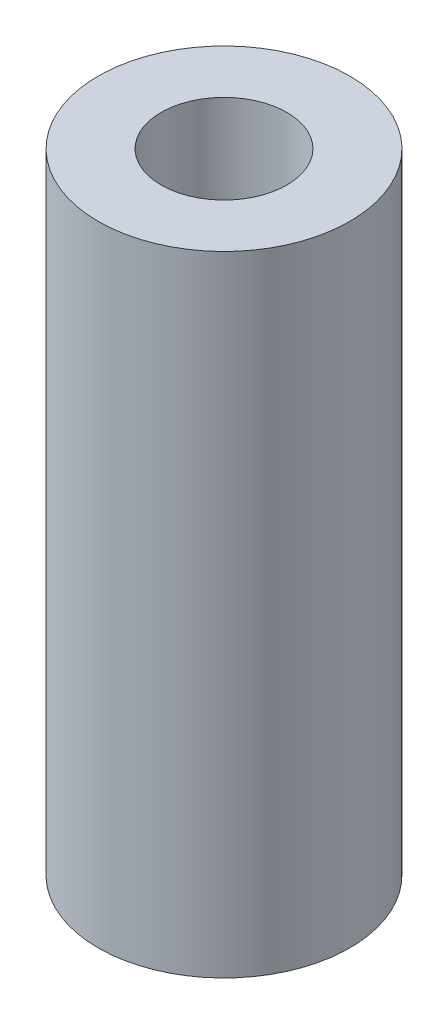
SolidWorks part; units mm, degrees
ref_plane "前视基准面" through (0, 0, 0) normal (0, 0, 1) x (1, 0, 0)
ref_plane "上视基准面" through (0, 0, 0) normal (0, 1, 0) x (1, 0, 0)
ref_plane "右视基准面" through (0, 0, 0) normal (1, 0, 0) x (0, 0, -1)
other "Configuration Table"
sketch "草图1" plane through (0, 0, 0) normal (0, 1, 0) x (1, 0, 0)
  circle A0 centre (0, 0) radius 3
  circle A1 centre (0, 0) radius 1.55
  dimension "D1" = 6
  dimension "D2" = 3.1
extrude "凸台-拉伸1" add sketch "草图1" along normal blind 15
sketch "草图2" plane through (0, 15, 0) normal (0, 1, 0) x (1, 0, 0)
  circle A0 centre (0, 0) radius 1.55
  circle A1 centre (0, 0) radius 1.5
  dimension "D1" = 3
extrude "凸台-拉伸2" add sketch "草图2" against normal blind 15
